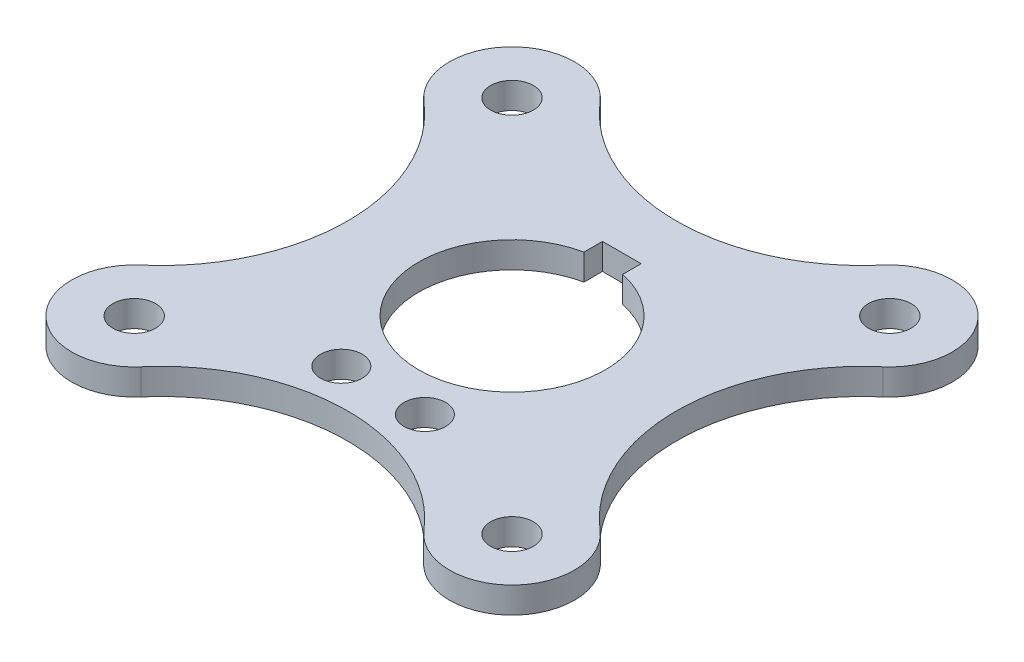
SolidWorks part; units mm, degrees
ref_plane "Front Plane" through (0, 0, 0) normal (0, 0, 1) x (1, 0, 0)
ref_plane "Top Plane" through (0, 0, 0) normal (0, 1, 0) x (1, 0, 0)
ref_plane "Right Plane" through (0, 0, 0) normal (1, 0, 0) x (0, 0, -1)
sketch "Sketch1" plane through (0, 0, 0) normal (0, 1, 0) x (1, 0, 0)
  line L0 (0, 0) -> (0, 11.3594) construction
  line L5 (0, 11.3594) -> (0, 13.3594) construction
  line L6 (2.3533, 13.3594) -> (-2.3533, 13.3594)
  line L7 (-2.3533, 13.3594) -> (-2.3533, 11.113)
  line L8 (21.1425, 21.1425) -> (22.981, 22.981) construction
  line L9 (2.3533, 13.3594) -> (2.3533, 11.113)
  circle A22 centre (0, 0) radius 32.5 construction
  circle A23 centre (22.981, 22.981) radius 2.6
  circle A24 centre (22.981, -22.981) radius 2.6
  circle A25 centre (-22.981, -22.981) radius 2.6
  arc A26 (-2.3533, 11.113) -> (2.3533, 11.113) centre (0, 0) ccw
  circle A28 centre (-22.981, 22.981) radius 2.6
  arc A29 (-17.2066, 27.9223) -> (-27.9223, 17.2066) centre (-22.981, 22.981) ccw
  arc A31 (27.9223, 17.2066) -> (17.2066, 27.9223) centre (22.981, 22.981) ccw
  arc A32 (17.2066, -27.9223) -> (27.9223, -17.2066) centre (22.981, -22.981) ccw
  arc A33 (-27.9223, -17.2066) -> (-17.2066, -27.9223) centre (-22.981, -22.981) ccw
  arc A38 (-27.9223, -17.2066) -> (-27.9223, 17.2066) centre (-42.6468, 0) ccw
  arc A39 (-17.2066, 27.9223) -> (17.2066, 27.9223) centre (0, 42.6468) ccw
  arc A40 (27.9223, 17.2066) -> (27.9223, -17.2066) centre (42.6468, 0) ccw
  arc A41 (17.2066, -27.9223) -> (-17.2066, -27.9223) centre (0, -42.6468) ccw
  circle A42 centre (22.981, -22.981) radius 7.6 construction
  circle A43 centre (-22.981, -22.981) radius 7.6 construction
  circle A44 centre (-22.981, 22.981) radius 7.6 construction
  circle A45 centre (22.981, 22.981) radius 7.6 construction
  point P0 (0, 0)
  point P2 (0, -20)
  point P8 (0, 13.3594)
  point P19 (0, 0)
  point P29 (0, 0)
  point P50 (0, 0)
  dimension "D1" = 22.7189
  dimension "D2" = 20
  dimension "D6" = 5
  dimension "D5" = 4
  dimension "D3" = 2
  dimension "D4" = 2.3533
  dimension "D8" = 4
extrude "Boss-Extrude1" add sketch "Sketch1" along normal blind 3.175
sketch "Sketch2" plane through (0, 3.175, 0) normal (0, 1, 0) x (1, 0, 0)
  line L0 (0, -11.3594) -> (0, -20) construction
  line L1 (-5.08, -15.6797) -> (5.08, -15.6797) construction
  arc A0 (-2.3533, 11.113) -> (2.3533, 11.113) centre (0, 0) ccw construction
  arc A1 (17.2066, -27.9223) -> (-17.2066, -27.9223) centre (0, -42.6468) ccw construction
  circle A2 centre (-5.08, -15.6797) radius 2.54
  circle A3 centre (5.08, -15.6797) radius 2.54
  point P11 (0, -15.6797)
  dimension "D1" = 5.08
  dimension "D2" = 10.16
extrude "Cut-Extrude1" cut sketch "Sketch2" against normal blind 10
